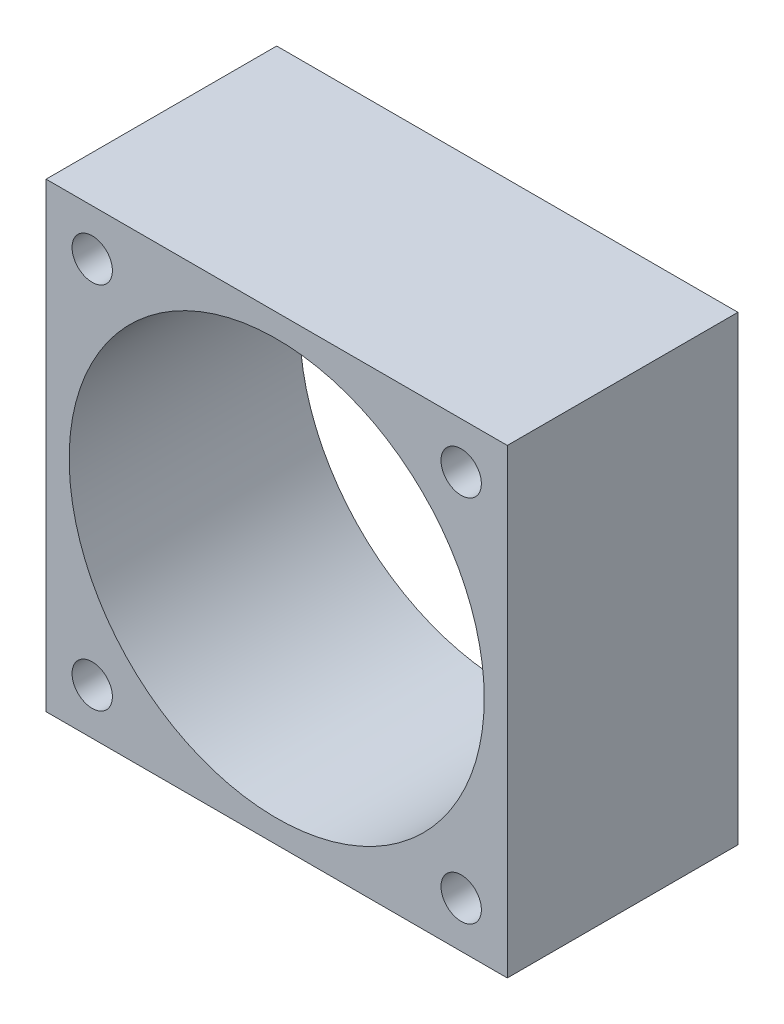
SolidWorks part; units mm, degrees
ref_plane "前视基准面" through (0, 0, 0) normal (0, 0, 1) x (1, 0, 0)
ref_plane "上视基准面" through (0, 0, 0) normal (0, 1, 0) x (1, 0, 0)
ref_plane "右视基准面" through (0, 0, 0) normal (1, 0, 0) x (0, 0, -1)
other "Configuration Table"
sketch "草图1" plane through (0, 0, 0) normal (0, 0, 1) x (1, 0, 0)
  line L1 (-30, 33) -> (10, 33)
  line L2 (-30, 33) -> (-30, 73)
  line L3 (-30, 73) -> (10, 73)
  line L4 (10, 33) -> (10, 73)
  circle A0 centre (-10, 53) radius 18
  circle A1 centre (-26, 37) radius 1.75
  circle A2 centre (-26, 69) radius 1.75
  circle A3 centre (6, 37) radius 1.75
  circle A4 centre (6, 69) radius 1.75
extrude "OFFICIAL_40x40x20_D3p5_pitch32" add sketch "草图1" along normal blind 20 from offset 0
